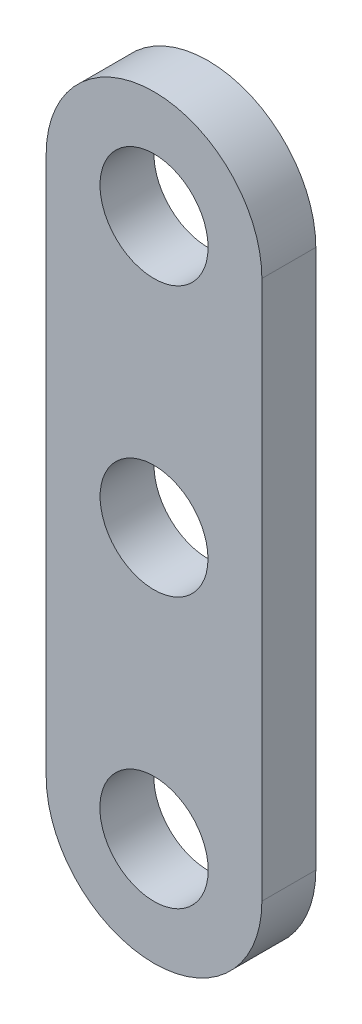
SolidWorks part; units mm, degrees
ref_plane "前视基准面" through (0, 0, 0) normal (0, 0, 1) x (1, 0, 0)
ref_plane "上视基准面" through (0, 0, 0) normal (0, 1, 0) x (1, 0, 0)
ref_plane "右视基准面" through (0, 0, 0) normal (1, 0, 0) x (0, 0, -1)
sketch "草图1" plane through (0, 0, 0) normal (0, 0, 1) x (1, 0, 0)
  line L0 (0, 0) -> (0, -30) construction
  line L3 (6, 0) -> (6, -30)
  line L4 (-6, 0) -> (-6, -30)
  arc A5 (6, 0) -> (-6, 0) centre (0, 0) ccw
  arc A6 (-6, -30) -> (6, -30) centre (0, -30) ccw
  circle A7 centre (0, 0) radius 3.0061
  circle A8 centre (0, -30) radius 3.014
  circle A9 centre (0, -15) radius 3.0009
  point P3 (0, -15)
  dimension "D1" = 6.0018
  dimension "D2" = 15
extrude "凸台-拉伸2" add sketch "草图1" along normal blind 3
